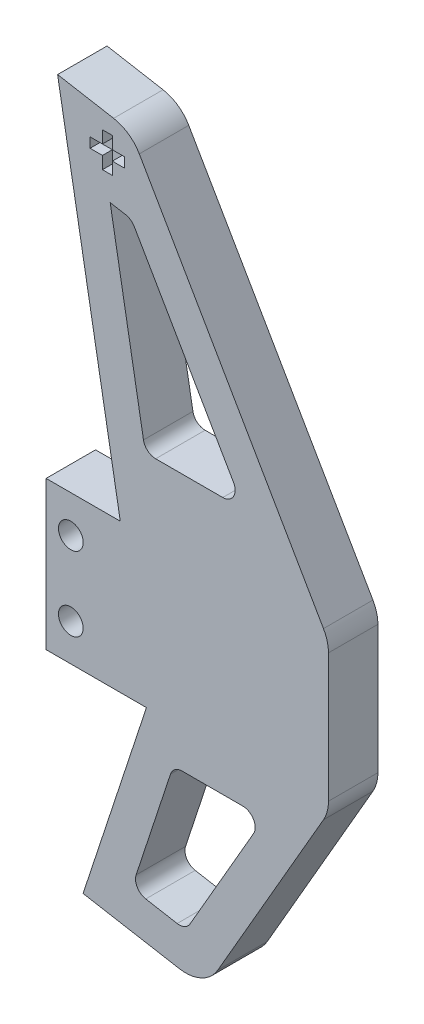
SolidWorks part; units mm, degrees
ref_plane "Ön Düzlem" through (0, 0, 0) normal (0, 0, 1) x (1, 0, 0)
ref_plane "Üst Düzlem" through (0, 0, 0) normal (0, 1, 0) x (1, 0, 0)
ref_plane "Sağ Düzlem" through (0, 0, 0) normal (1, 0, 0) x (0, 0, -1)
sketch "Çizim1" plane through (0, 0, 0) normal (0, 0, 1) x (1, 0, 0)
  line L0 (-26.0665, 76.7966) -> (-11.2943, 74.1919)
  line L1 (-11.2943, 74.1919) -> (28.7057, 4.9099)
  line L2 (28.7057, 4.9099) -> (28.7057, -25.0901)
  line L3 (28.7057, -25.0901) -> (3.7057, -68.3914)
  line L7 (7.341, 74.1919) -> (-43.0209, 74.1919) construction
  line L8 (37.8011, 4.9099) -> (-16.5724, 4.9099) construction
  line L9 (39.5541, -25.0901) -> (-4.3598, -25.0901) construction
  line L10 (3.7057, -68.3914) -> (-20.9145, -64.0502)
  line L11 (14.6456, -68.3914) -> (-21.4589, -68.3914) construction
  line L12 (28.7057, -10.0901) -> (-81.536, -10.0901) construction
  line L14 (-13.3909, 4.9099) -> (-26.0665, 76.7966)
  line L15 (-13.3909, 4.9099) -> (-28.3909, 4.9099)
  line L16 (-28.3909, 4.9099) -> (-28.3909, -25.0901)
  line L17 (-28.3909, -25.0901) -> (-8.1011, -25.0901)
  line L18 (-13.3909, 4.9099) -> (-0.5827, -67.7289) construction
  line L19 (-20.9145, -64.0502) -> (-8.1011, -25.0901)
  line L20 (-8.1011, -25.0901) -> (-22.7831, -25.0901) construction
  circle A0 centre (-23.3909, -2.5901) radius 2.5
  circle A1 centre (-23.3909, -17.5901) radius 2.5
  dimension "D12" = 5
  dimension "D13" = 5
  dimension "D1" = 170
  dimension "D2" = 15
  dimension "D3" = 30
  dimension "D4" = 80
  dimension "D5" = 50
  dimension "D6" = 60
  dimension "D7" = 60
  dimension "D8" = 10
  dimension "D9" = 25
  dimension "D10" = 80
  dimension "D11" = 15
  dimension "D14" = 7.5
  dimension "D15" = 7.5
  dimension "D16" = 5
  dimension "D17" = 5
extrude "Yükseklik-Ekstrüzyon1" add sketch "Çizim1" along normal blind 10
fillet "Radyus1" radius 7.5 1 edges at (-11.2943, 74.1919, 5)
fillet "Radyus2" radius 7.5 3 edges at (3.7057, -68.3914, 5) (28.7057, -25.0901, 5) (28.7057, 4.9099, 5)
sketch "Çizim2" plane through (0, 0, 10) normal (0, 0, 1) x (1, 0, 0)
  line L0 (-15.4345, 59.6905) -> (-8.6987, 21.4901)
  line L1 (-6.2367, 19.4242) -> (7.3354, 19.4242)
  line L2 (9.5005, 23.1742) -> (-10.5627, 57.9247)
  line L4 (-12.2937, 59.1367) -> (-15.4345, 59.6905)
  line L5 (-26.0665, 76.7966) -> (-13.3909, 4.9099) construction
  line L6 (27.7009, 6.6502) -> (-9.5457, 71.1631) construction
  line L7 (-14.7385, 74.7992) -> (-26.0665, 76.7966) construction
  line L8 (-8.2422, -58.669) -> (-1.8877, -59.7895)
  line L9 (0.7115, -58.5774) -> (13.5502, -36.3401)
  line L10 (11.3852, -32.5901) -> (-0.863, -32.5901)
  line L11 (-3.2378, -34.3091) -> (-10.1829, -55.4259)
  line L12 (-8.1011, -25.0901) -> (-20.9145, -64.0502) construction
  line L13 (6.3314, -63.8434) -> (27.7009, -26.8305) construction
  line L14 (-20.9145, -64.0502) -> (-1.4661, -67.4795) construction
  line L15 (-28.3909, -25.0901) -> (-8.1011, -25.0901) construction
  arc A0 (-8.6987, 21.4901) -> (-6.2367, 19.4242) centre (-6.2367, 21.9242) ccw
  arc A1 (7.3354, 19.4242) -> (9.5005, 23.1742) centre (7.3354, 21.9242) ccw
  arc A2 (-10.5627, 57.9247) -> (-12.2937, 59.1367) centre (-12.7278, 56.6747) ccw
  arc A3 (-8.2422, -58.669) -> (-10.1829, -55.4259) centre (-7.808, -56.207) cw
  arc A4 (-1.8877, -59.7895) -> (0.7115, -58.5774) centre (-1.4536, -57.3274) ccw
  arc A5 (13.5502, -36.3401) -> (11.3852, -32.5901) centre (11.3852, -35.0901) ccw
  arc A6 (-0.863, -32.5901) -> (-3.2378, -34.3091) centre (-0.863, -35.0901) ccw
  point P13 (-8.3345, 19.4242)
  point P16 (11.6655, 19.4242)
  dimension "D5" = 2.5
  dimension "D10" = 2.5
  dimension "D1" = 7.5
  dimension "D2" = 7.5
  dimension "D3" = 15
  dimension "D4" = 20
  dimension "D6" = 7.5
  dimension "D7" = 7.5
  dimension "D8" = 7.5
  dimension "D9" = 7.5
extrude "Kes-Ekstrüzyon1" cut sketch "Çizim2" against normal blind 10
sketch "Çizim3" plane through (0, 0, 10) normal (0, 0, 1) x (1, 0, 0)
  line L0 (-17, 71.6678) -> (-15, 71.6678)
  line L1 (-15, 71.6678) -> (-15, 69.1678)
  line L2 (-15, 69.1678) -> (-12.5, 69.1678)
  line L3 (-12.5, 69.1678) -> (-12.5, 67.1678)
  line L4 (-12.5, 67.1678) -> (-15, 67.1678)
  line L5 (-15, 67.1678) -> (-15, 64.6678)
  line L6 (-15, 64.6678) -> (-17, 64.6678)
  line L7 (-17, 64.6678) -> (-17, 67.1678)
  line L8 (-17, 67.1678) -> (-19.5, 67.1678)
  line L9 (-19.5, 67.1678) -> (-19.5, 69.1678)
  line L10 (-19.5, 69.1678) -> (-17, 69.1678)
  line L11 (-17, 69.1678) -> (-17, 71.6678)
  dimension "D1" = 2.5
  dimension "D2" = 2
  dimension "D3" = 2
  dimension "D4" = 2
  dimension "D5" = 2
  dimension "D6" = 2.5
  dimension "D7" = 2.5
  dimension "D8" = 2.5
  dimension "D9" = 2.5
  dimension "D10" = 12.5
extrude "Kes-Ekstrüzyon2" cut sketch "Çizim3" against normal blind 2
